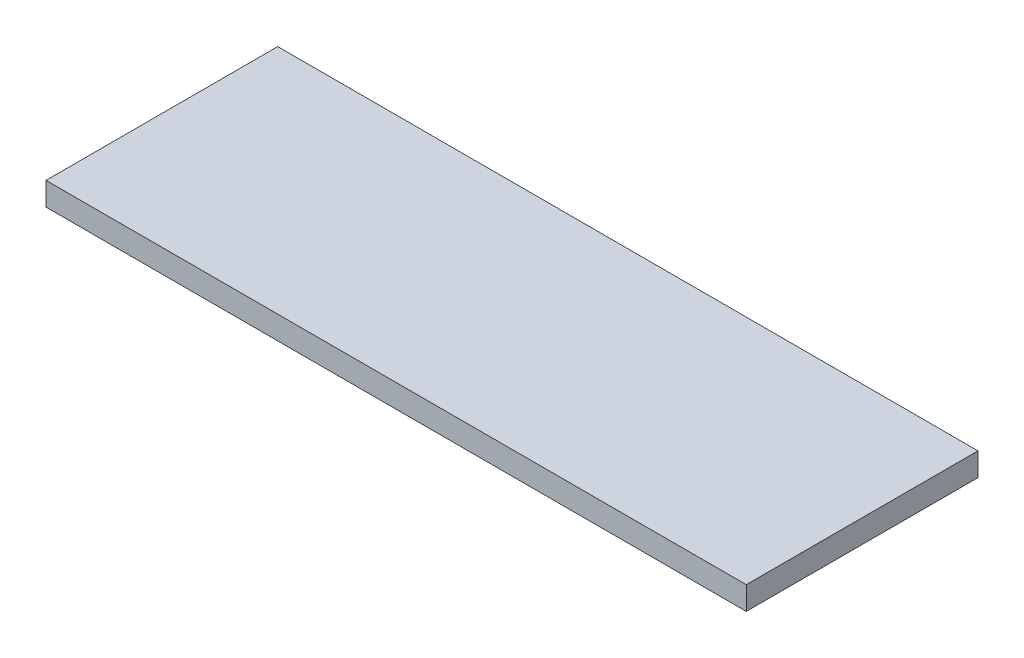
SolidWorks part; units mm, degrees
material "AISI 1020"
ref_plane "Front Plane" through (0, 0, 0) normal (0, 0, 1) x (1, 0, 0)
ref_plane "Top Plane" through (0, 0, 0) normal (0, 1, 0) x (1, 0, 0)
ref_plane "Right Plane" through (0, 0, 0) normal (1, 0, 0) x (0, 0, -1)
sketch "Sketch1" plane through (0, 0, 0) normal (0, 1, 0) x (1, 0, 0)
  line L1 (-150.6285, -16.5202) -> (99.3715, -16.5202)
  line L2 (-150.6285, -16.5202) -> (-150.6285, -56.5202)
  line L3 (-150.6285, -56.5202) -> (99.3715, -56.5202)
  line L4 (99.3715, -16.5202) -> (99.3715, -56.5202)
  dimension "D1" = 40
  dimension "D2" = 250
extrude "Boss-Extrude1" add sketch "Sketch1" along normal blind 4
sketch "Sketch3" plane through (0, 4, 0) normal (0, 1, 0) x (1, 0, 0)
  line L1 (-29.7473, -84.4038) -> (104.2238, -84.4038)
  line L2 (-29.7473, -84.4038) -> (-29.7473, -5.1018)
  line L3 (-29.7473, -5.1018) -> (104.2238, -5.1018)
  line L4 (104.2238, -84.4038) -> (104.2238, -5.1018)
  line L5 (-32.7473, 164.9107) -> (-32.7473, -61.805) construction
  dimension "D1" = 3
extrude "Cut-Extrude2" cut sketch "Sketch3" against normal blind 10 contours L1 L4 L3 L2
